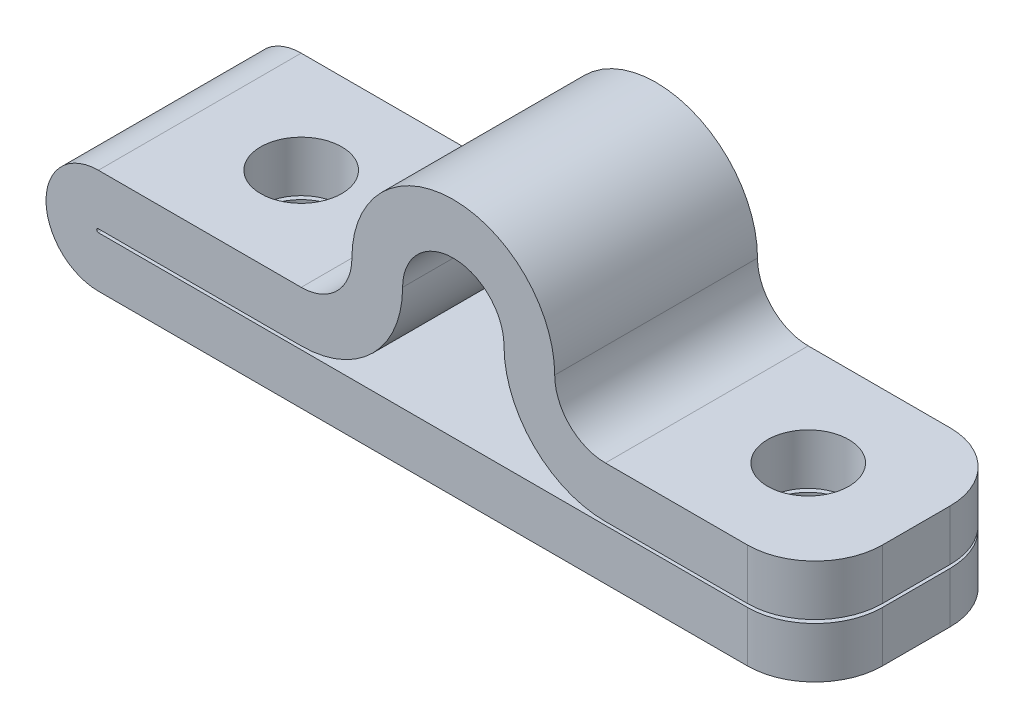
SolidWorks part; units mm, degrees
material "PLA"
ref_plane "Plan de face" through (0, 0, 0) normal (0, 0, 1) x (1, 0, 0)
ref_plane "Plan de dessus" through (0, 0, 0) normal (0, 1, 0) x (1, 0, 0)
ref_plane "Plan de droite" through (0, 0, 0) normal (1, 0, 0) x (0, 0, -1)
sketch "Sketch1" plane through (0, 0, 0) normal (0, 0, 1) x (1, 0, 0)
  line L0 (-10.5, 0) -> (10.7, 0)
  line L1 (10.7, 0) -> (10.7, 1.5)
  line L2 (10.7, 1.5) -> (-10.5, 1.5)
  line L3 (-10.5, 1.6) -> (-4.5, 1.6)
  line L4 (4.5, 1.6) -> (10.7, 1.6)
  line L5 (-7.5, 8.5621) -> (-7.5, -5.9396) construction
  line L6 (7.5, -6.0625) -> (7.5, 8.685) construction
  line L7 (6.3, 3.1) -> (6.3, 0) construction
  line L8 (8.7, 3.1) -> (8.7, 0) construction
  line L9 (-6.3, 3.1) -> (-6.3, 0) construction
  line L10 (-8.7, 3.1) -> (-8.7, 0) construction
  line L11 (10.7, 1.6) -> (10.7, 3.1)
  line L12 (10.7, 3.1) -> (4.5, 3.1)
  line L14 (-10.5, 3.1) -> (-4.5, 3.1)
  arc A0 (-10.5, 0) -> (-10.5, 3.1) centre (-10.5, 1.55) cw
  arc A1 (-10.5, 1.5) -> (-10.5, 1.6) centre (-10.5, 1.55) cw
  arc A2 (4.5, 1.6) -> (1.5, 4.6) centre (4.5, 4.6) cw
  arc A3 (1.5, 4.6) -> (0, 6.1) centre (0, 4.6) ccw
  arc A4 (0, 6.1) -> (-1.5, 4.6) centre (0, 4.6) ccw
  arc A5 (-1.5, 4.6) -> (-4.5, 1.6) centre (-4.5, 4.6) cw
  arc A6 (-4.5, 3.1) -> (-3, 4.6) centre (-4.5, 4.6) ccw
  arc A7 (-3, 4.6) -> (0, 7.6) centre (0, 4.6) cw
  arc A8 (4.5, 3.1) -> (3, 4.6) centre (4.5, 4.6) cw
  arc A9 (3, 4.6) -> (0, 7.6) centre (0, 4.6) ccw
  point P29 (7.5, 3.1)
  point P56 (-7.5, 3.1)
  dimension "D12" = 3
  dimension "D13" = 3
  dimension "D1" = 1.5
  dimension "D2" = 15
  dimension "D3" = 7.5
  dimension "D4" = 2.4
  dimension "D5" = 1.2
  dimension "D6" = 2.4
  dimension "D7" = 1.2
  dimension "D8" = 2
  dimension "D9" = 0.1
  dimension "D10" = 3
  dimension "D11" = 3
extrude "Boss-Extrude1" add sketch "Sketch1" along normal mid plane 6 contours A8 A9 A7 A6 L14 A0 L0 L1 L2 A1 L3 A5 A4 A3 A2 L4 L11 L12
hole_wizard "M2 Clearance Hole1" positions "Sketch4" profile "Sketch5" hole size "M2" standard "ANSI Metric" end condition through all
sketch "Sketch4" plane through (0, 3.1, 0) normal (0, 1, 0) x (1, 0, 0)
  line L0 (-10.5, 0) -> (10.7, 0) construction
  line L1 (10.7, 0) -> (4.5, 0) construction
  point P0 (-7.5, 0)
  point P4 (7.5, 0)
sketch "Sketch5" plane through (-7.5, 3.1, 0) normal (1, 0, 0) x (0, 0, 1)
  line L0 (0, 0) -> (0, 3.1)
  line L1 (0, 3.1) -> (1.2, 3.1)
  line L2 (1.2, 3.1) -> (1.2, 0)
  line L5 (1.2, 0) -> (0, 0)
  line L11 (0, -6.35) -> (0, 107.95) construction
  dimension "Thru Hole Dia." = 2.4
  dimension "Thru Hole Depth" = 3.1
fillet "Fillet1" radius 2 4 edges at (10.7, 0.75, -3) (10.7, 2.35, -3) (10.7, 2.35, 3) (10.7, 0.75, 3)
